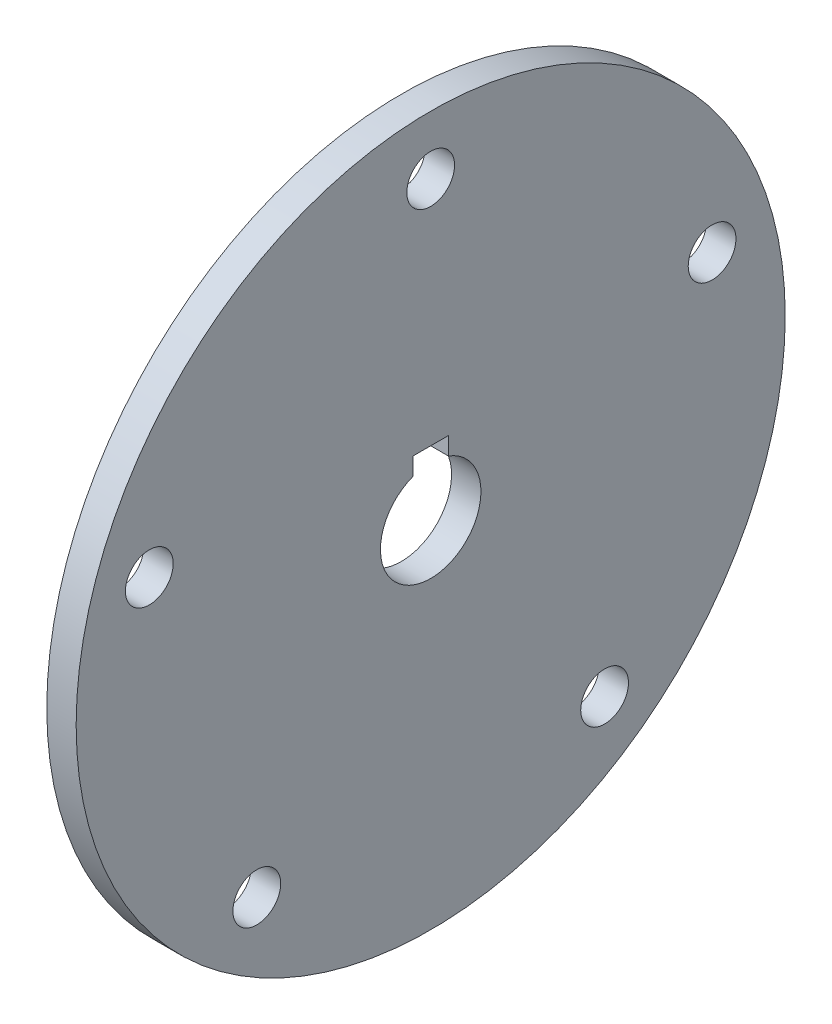
SolidWorks part; units mm, degrees
material "Alloy Steel"
ref_plane "Front Plane" through (0, 0, 0) normal (0, 0, 1) x (1, 0, 0)
ref_plane "Top Plane" through (0, 0, 0) normal (0, 1, 0) x (1, 0, 0)
ref_plane "Right Plane" through (0, 0, 0) normal (1, 0, 0) x (0, 0, -1)
sketch "Sketch1" plane through (0, 0, 0) normal (1, 0, 0) x (0, 0, -1)
  circle A0 centre (0, 0) radius 60.325
  dimension "D1" = 120.65
extrude "Boss-Extrude1" add sketch "Sketch1" along normal mid plane 5
sketch "Sketch2" plane through (-2.5, 0, 0) normal (-1, 0, 0) x (0, 0, 1)
  line L0 (0, 60.325) -> (0, -60.325) construction
  circle A1 centre (0, 0) radius 60.325 construction
  circle A16 centre (0, 50.343) radius 4.064
  circle A17 centre (47.879, 15.5568) radius 4.064
  circle A18 centre (29.5908, -40.7283) radius 4.064
  circle A19 centre (-29.5908, -40.7283) radius 4.064
  circle A20 centre (-47.879, 15.5568) radius 4.064
extrude "Cut-Extrude1" cut sketch "Sketch2" against normal through all
sketch "Sketch8" plane through (2.5, 0, 0) normal (1, 0, 0) x (0, 0, -1)
  line L0 (0, 5.55) -> (0, 8.55) construction
  line L10 (0, 8.55) -> (0, 11.0064) construction
  line L11 (0, 11.0064) -> (-3, 11.0064)
  line L14 (-3, 11.0064) -> (-3, 8.0064)
  line L15 (0, 11.0064) -> (3, 11.0064)
  line L16 (3, 11.0064) -> (3, 8.0064)
  line L17 (-3, 8.0064) -> (3, 8.0064) construction
  arc A1 (-3, 8.0064) -> (3, 8.0064) centre (0, 0) ccw
  dimension "D1" = 17.1
  dimension "D2" = 3
  dimension "D3" = 3
extrude "Cut-Extrude4" cut sketch "Sketch8" against normal through all
